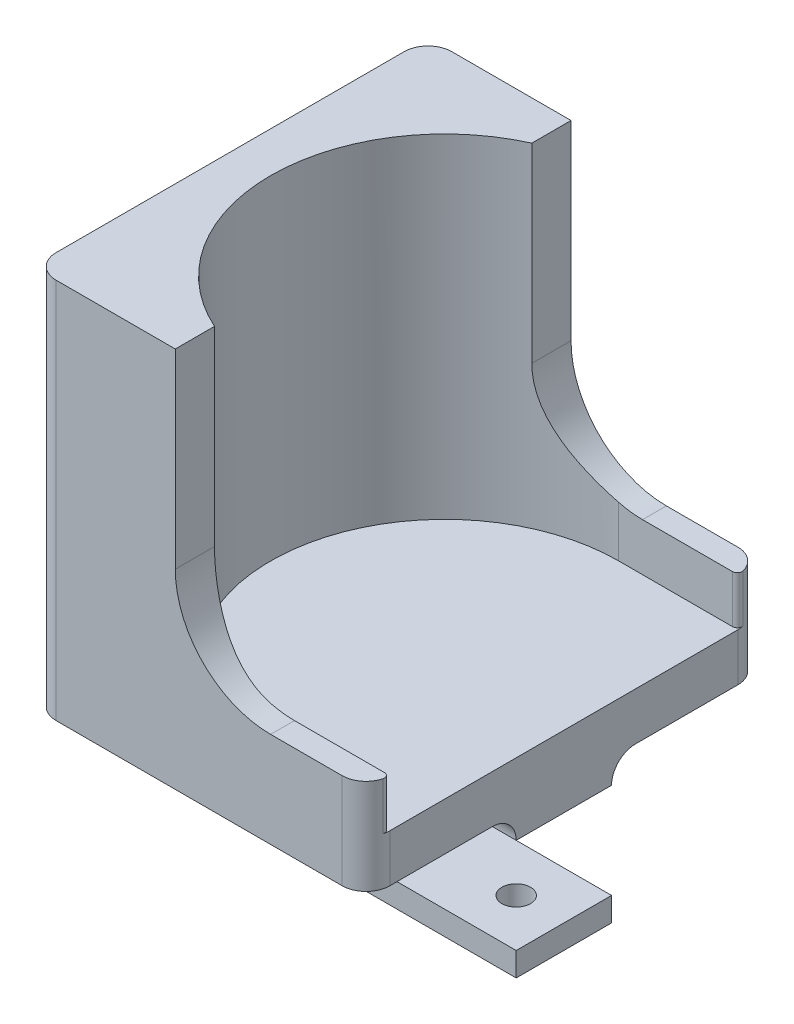
SolidWorks part; units mm, degrees
ref_plane "前基準面" through (0, 0, 0) normal (0, 0, 1) x (1, 0, 0)
ref_plane "上基準面" through (0, 0, 0) normal (0, 1, 0) x (1, 0, 0)
ref_plane "右基準面" through (0, 0, 0) normal (1, 0, 0) x (0, 0, -1)
sketch "草圖2" plane through (0, 0, 0) normal (0, 1, 0) x (1, 0, 0)
  line L1 (-30, 41.5) -> (30, 41.5)
  line L2 (-35, 36.5) -> (-35, -36.5)
  line L3 (-30, -41.5) -> (30, -41.5)
  line L4 (35, 36.5) -> (35, -36.5)
  line L5 (-35, 41.5) -> (35, -41.5) construction
  line L6 (-35, -41.5) -> (35, 41.5) construction
  arc A0 (30, 41.5) -> (35, 36.5) centre (30, 36.5) cw
  arc A1 (30, -41.5) -> (35, -36.5) centre (30, -36.5) ccw
  arc A2 (-35, -36.5) -> (-30, -41.5) centre (-30, -36.5) ccw
  arc A3 (-30, 41.5) -> (-35, 36.5) centre (-30, 36.5) ccw
  point P0 (0, 0)
  dimension "D3" = 5
  dimension "D1" = 70
  dimension "D2" = 83
extrude "填料-伸長1" add sketch "草圖2" along normal blind 10
sketch "草圖3" plane through (0, 10, 0) normal (0, 1, 0) x (1, 0, 0)
  line L0 (0, -45.9482) -> (0, 50.4274) construction
  line L1 (64.5067, 0) -> (-60.7671, 0) construction
  line L4 (30, 41.5) -> (-30, 41.5) construction
  line L7 (30, 41.5) -> (-30, 41.5)
  line L8 (-35, 36.5) -> (-35, -36.5)
  line L9 (-30, -41.5) -> (30, -41.5)
  line L10 (35, -36.5) -> (35, 36.5)
  line L12 (-35, 36.5) -> (-35, -36.5)
  line L13 (-30, -41.5) -> (30, -41.5)
  line L19 (30, 41.5) -> (-30, 41.5)
  line L20 (10, -36.5) -> (10, 36.5) construction
  line L22 (33.873, -36.5) -> (10, -36.5)
  line L25 (10, 36.5) -> (33.873, 36.5)
  arc A2 (-30, 41.5) -> (-35, 36.5) centre (-30, 36.5) ccw construction
  arc A3 (-30, 41.5) -> (-35, 36.5) centre (-30, 36.5) ccw
  arc A6 (35, 36.5) -> (30, 41.5) centre (30, 36.5) ccw
  arc A7 (-30, 41.5) -> (-35, 36.5) centre (-30, 36.5) ccw
  arc A8 (-35, -36.5) -> (-30, -41.5) centre (-30, -36.5) ccw
  arc A9 (30, -41.5) -> (35, -36.5) centre (30, -36.5) ccw
  arc A12 (-35, -36.5) -> (-30, -41.5) centre (-30, -36.5) ccw
  arc A13 (30, -41.5) -> (34.8412, -37.75) centre (30, -36.5) ccw
  arc A19 (30, 41.5) -> (34.8412, 37.75) centre (30, 36.5) cw
  arc A20 (10, 36.5) -> (10, -36.5) centre (10, 0) ccw
  arc A21 (34.8412, 37.75) -> (33.873, 36.5) centre (33.873, 37.5) cw
  arc A24 (33.873, -36.5) -> (34.8412, -37.75) centre (33.873, -37.5) cw
  point P9 (10, -36.5)
  point P27 (34.8412, -37.75)
  point P29 (33.873, 37.5)
  point P30 (0, 0)
  point P31 (0, 0)
  point P34 (-35, 0)
  point P35 (34.999, -36.6022)
  point P42 (-35, 35)
  dimension "D1" = 1
  dimension "D3" = 25
  dimension "D4" = 1
  dimension "D5" = 36.5
  dimension "D2" = 0
extrude "填料-伸長2" add sketch "草圖3" along normal blind 70
sketch "草圖6" plane through (0, 0, 0) normal (0, -1, 0) x (1, 0, 0)
  line L7 (-35, -36.5) -> (-35, 36.5) construction
  line L8 (35, 10) -> (-35, 10)
  line L9 (35, 10) -> (35, -10)
  line L10 (35, -10) -> (-35, -10)
  line L11 (-35, 10) -> (-35, -10)
  line L12 (35, 10) -> (-35, -10) construction
  line L13 (35, -10) -> (-35, 10) construction
  point P0 (0, 0)
  point P8 (0, 0)
  dimension "D1" = 20
  dimension "D2" = 70
extrude "填料-伸長3" add sketch "草圖6" along normal blind 30
sketch "草圖8" plane through (0, -30, 0) normal (0, -1, 0) x (1, 0, 0)
  line L0 (-50.5753, 0) -> (52.502, 0) construction
  line L1 (35, -10) -> (35, 10) construction
  circle A0 centre (25, 0) radius 3
  dimension "D1" = 6
  dimension "D2" = 10
extrude "除料-伸長5" cut sketch "草圖8" against normal blind 15
fillet "圓角2" radius 5 2 edges at (0, 0, 10) (0, 0, -10)
sketch "草圖9" plane through (35, 0, 0) normal (1, 0, 0) x (0, 0, -1)
  line L0 (-15, 0) -> (15, 0) construction
  line L2 (-10, -30) -> (-10, -5) construction
  line L3 (-10, -5) -> (10, -5)
  line L4 (10, -30) -> (10, -5) construction
  line L11 (-10, -25) -> (10, -25)
  line L13 (10, -30) -> (-10, -30) construction
  line L14 (-10, -5) -> (-10, -25)
  line L15 (10, -25) -> (10, -5)
  arc A0 (-10, -5) -> (-15, 0) centre (-15, -5) ccw construction
  arc A1 (15, 0) -> (10, -5) centre (15, -5) ccw construction
  arc A2 (-10, -5) -> (-15, 0) centre (-15, -5) ccw construction
  arc A3 (15, 0) -> (10, -5) centre (15, -5) ccw construction
  dimension "D1" = 5
  dimension "D2" = 5
extrude "除料-伸長6" cut sketch "草圖9" against normal blind 30
fillet "圓角4" radius 2 2 edges at (5, -25, 0) (5, -5, 0)
sketch "草圖10" plane through (0, 0, 41.5) normal (0, 0, 1) x (1, 0, 0)
  line L0 (35, 80) -> (-5, 80)
  line L1 (-5, 80) -> (-5, 40)
  line L2 (35, 80) -> (35, 20)
  line L4 (15, 20) -> (15, 40.3321) construction
  line L5 (15, 20) -> (35, 20)
  line L8 (-30, 80) -> (30, 80) construction
  line L9 (-35, 80) -> (-35, 0) construction
  line L10 (-30, 0) -> (30, 0) construction
  arc A0 (15, 20) -> (-5, 40) centre (15, 40) cw
  point P0 (4.5463, 0)
  dimension "D1" = 20
  dimension "D2" = 40
  dimension "D3" = 20
  dimension "D4" = 30
extrude "除料-伸長7" cut sketch "草圖10" against normal through all
